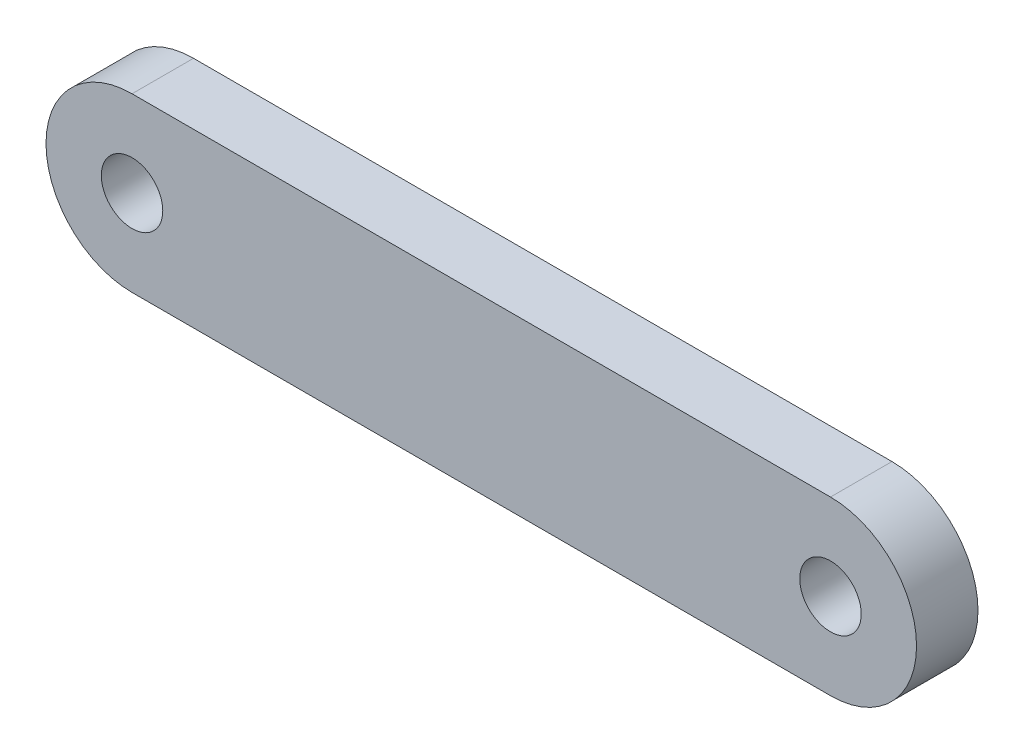
SolidWorks part; units mm, degrees
ref_plane "Front Plane" through (0, 0, 0) normal (0, 0, 1) x (1, 0, 0)
ref_plane "Top Plane" through (0, 0, 0) normal (0, 1, 0) x (1, 0, 0)
ref_plane "Right Plane" through (0, 0, 0) normal (1, 0, 0) x (0, 0, -1)
sketch "Sketch1" plane through (0, 0, 0) normal (0, 0, 1) x (1, 0, 0)
  line L0 (-18.7122, -8.6365) -> (53.4568, -8.6365)
  line L1 (-18.7122, 9.1435) -> (53.4568, 9.1435)
  line L2 (-18.7122, -8.6365) -> (53.4568, 9.1435) construction
  line L3 (-18.7122, 9.1435) -> (53.4568, -8.6365) construction
  arc A0 (-18.7122, 9.1435) -> (-18.7122, -8.6365) centre (-18.7122, 0.2535) ccw
  arc A1 (53.4568, 9.1435) -> (53.4568, -8.6365) centre (53.4568, 0.2535) cw
  circle A2 centre (-18.7122, 0.2535) radius 3.175
  circle A3 centre (53.4568, 0.2535) radius 3.175
  point P0 (17.3723, 0.2535)
  dimension "D3" = 6.35
  dimension "D1" = 72.169
  dimension "D2" = 17.78
extrude "Boss-Extrude1" add sketch "Sketch1" along normal blind 6.35
